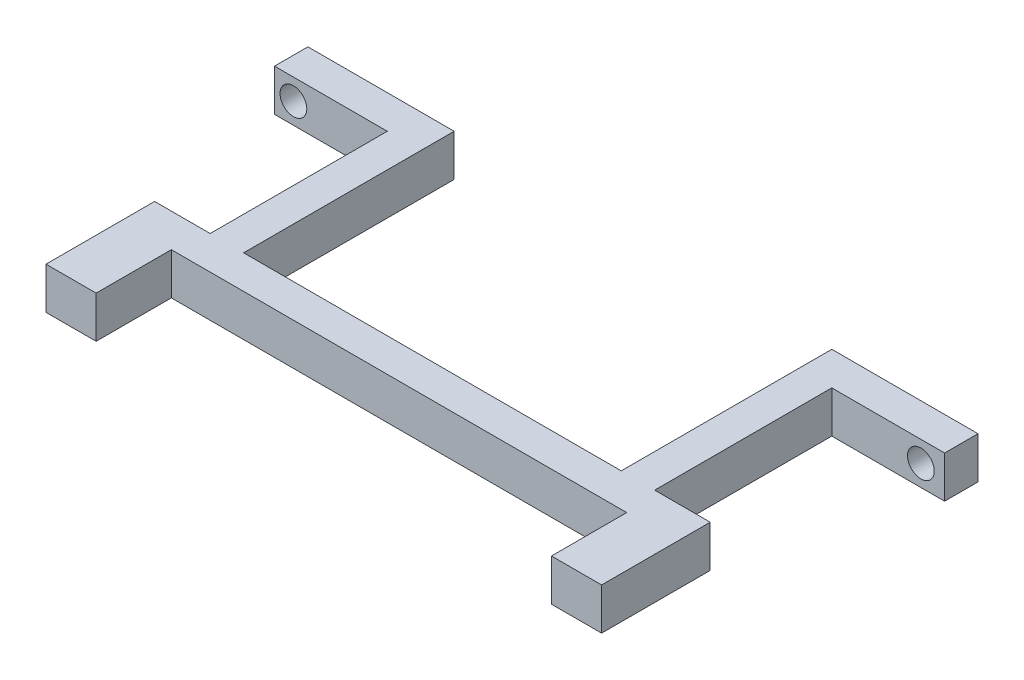
SolidWorks part; units mm, degrees
ref_plane "Front Plane" through (0, 0, 0) normal (0, 0, 1) x (1, 0, 0)
ref_plane "Top Plane" through (0, 0, 0) normal (0, 1, 0) x (1, 0, 0)
ref_plane "Right Plane" through (0, 0, 0) normal (1, 0, 0) x (0, 0, -1)
sketch "Sketch1" plane through (0, 0, 0) normal (0, 0, 1) x (1, 0, 0)
  line L1 (-91.6826, 14.4689) -> (-41.4826, 14.4689)
  line L2 (-91.6826, 14.4689) -> (-91.6826, 9.4689)
  line L3 (-91.6826, 9.4689) -> (-41.4826, 9.4689)
  line L4 (-41.4826, 14.4689) -> (-41.4826, 9.4689)
  dimension "D1" = 50.2
  dimension "D2" = 5
extrude "Boss-Extrude1" add sketch "Sketch1" along normal blind 26.2
sketch "Sketch2" plane through (0, 9.4689, 0) normal (0, -1, 0) x (1, 0, 0)
  line L0 (2.75, 0) -> (-2.75, 0) construction
  line L1 (-89.1826, 23.6998) -> (-43.9826, 23.6998)
  line L2 (-89.1826, 23.6998) -> (-89.1826, 0)
  line L3 (-89.1826, 0) -> (-43.9826, 0)
  line L4 (-43.9826, 23.6998) -> (-43.9826, 0)
  line L5 (-91.6826, 26.2) -> (-91.6826, 0) construction
  dimension "D1" = 45.2
  dimension "D2" = 2.5
extrude "Cut-Extrude1" cut sketch "Sketch2" against normal blind 26.2
sketch "Sketch4" plane through (0, 9.4689, 0) normal (0, -1, 0) x (1, 0, 0)
  line L1 (-91.6826, 26.2) -> (-90.1826, 26.2)
  line L2 (-91.6826, 26.2) -> (-91.6826, 2)
  line L3 (-91.6826, 2) -> (-90.1826, 2)
  line L4 (-90.1826, 26.2) -> (-90.1826, 2)
  dimension "D1" = 24.2
  dimension "D2" = 1.5
extrude "Cut-Extrude2" cut sketch "Sketch4" against normal blind 26.2
sketch "Sketch5" plane through (-91.6826, 0, 0) normal (-1, 0, 0) x (0, 0, 1)
  line L0 (0, -2.75) -> (0, 2.75) construction
  line L1 (2, 14.4689) -> (0, 14.4689)
  line L2 (2, 14.4689) -> (2, 9.4689)
  line L3 (2, 9.4689) -> (0, 9.4689)
  line L4 (0, 14.4689) -> (0, 9.4689)
  line L5 (2, 9.4689) -> (0, 9.4689) construction
extrude "Boss-Extrude2" add sketch "Sketch5" along normal blind 3
sketch "Sketch7" plane through (0, 9.4689, 0) normal (0, -1, 0) x (1, 0, 0)
  line L1 (-41.4826, 26.2) -> (-42.9826, 26.2)
  line L2 (-41.4826, 26.2) -> (-41.4826, 2)
  line L3 (-41.4826, 2) -> (-42.9826, 2)
  line L4 (-42.9826, 26.2) -> (-42.9826, 2)
  dimension "D1" = 1.5
  dimension "D2" = 24.2
extrude "Cut-Extrude3" cut sketch "Sketch7" against normal blind 23
sketch "Sketch8" plane through (0, 9.4689, 0) normal (0, -1, 0) x (1, 0, 0)
  line L1 (-89.1826, 23.6998) -> (-43.9826, 23.6998)
  line L2 (-89.1826, 23.6998) -> (-89.1826, 25.1998)
  line L3 (-89.1826, 25.1998) -> (-43.9826, 25.1998)
  line L4 (-43.9826, 23.6998) -> (-43.9826, 25.1998)
  dimension "D1" = 45.2
  dimension "D2" = 1.5
extrude "Cut-Extrude4" cut sketch "Sketch8" against normal blind 23
sketch "Sketch9" plane through (-41.4826, 0, 0) normal (1, 0, 0) x (0, 0, -1)
  line L0 (0, 2.75) -> (0, -2.75) construction
  line L1 (-2, 14.4689) -> (0, 14.4689)
  line L2 (-2, 14.4689) -> (-2, 9.4689)
  line L3 (-2, 9.4689) -> (0, 9.4689)
  line L4 (0, 14.4689) -> (0, 9.4689)
  line L5 (-2, 9.4689) -> (0, 9.4689) construction
extrude "Boss-Extrude3" add sketch "Sketch9" along normal blind 3
sketch "Sketch11" plane through (-38.4826, 0, 0) normal (1, 0, 0) x (0, 0, -1)
  line L0 (0, 2.75) -> (0, -2.75) construction
  line L1 (-2, 14.4689) -> (0, 14.4689)
  line L2 (-2, 14.4689) -> (-2, 9.4689)
  line L3 (-2, 9.4689) -> (0, 9.4689)
  line L4 (0, 14.4689) -> (0, 9.4689)
  line L5 (-2, 9.4689) -> (0, 9.4689) construction
extrude "Boss-Extrude4" add sketch "Sketch11" along normal blind 2
sketch "Sketch12" plane through (-94.6826, 0, 0) normal (-1, 0, 0) x (0, 0, 1)
  line L0 (0, -2.75) -> (0, 2.75) construction
  line L1 (2, 14.4689) -> (0, 14.4689)
  line L2 (2, 14.4689) -> (2, 9.4716)
  line L3 (2, 9.4716) -> (0, 9.4716)
  line L4 (0, 14.4689) -> (0, 9.4716)
extrude "Boss-Extrude5" add sketch "Sketch12" along normal blind 2
sketch "Sketch15" plane through (-90.1826, 0, 0) normal (-1, 0, 0) x (0, 0, 1)
  line L0 (2, 9.4689) -> (26.2, 9.4689) construction
  line L1 (26.2, 14.4689) -> (25.2, 14.4689)
  line L2 (26.2, 14.4689) -> (26.2, 9.4689)
  line L3 (26.2, 9.4689) -> (25.2, 9.4689)
  line L4 (25.2, 14.4689) -> (25.2, 9.4689)
  dimension "D1" = 1
extrude "Boss-Extrude6" add sketch "Sketch15" along normal blind 4.65
sketch "Sketch16" plane through (-42.9826, 0, 0) normal (1, 0, 0) x (0, 0, -1)
  line L0 (-26.2, 9.4689) -> (-2, 9.4689) construction
  line L1 (-26.2, 14.4689) -> (-25.2, 14.4689)
  line L2 (-26.2, 14.4689) -> (-26.2, 9.4689)
  line L3 (-26.2, 9.4689) -> (-25.2, 9.4689)
  line L4 (-25.2, 14.4689) -> (-25.2, 9.4689)
  dimension "D1" = 1
extrude "Boss-Extrude7" add sketch "Sketch16" along normal blind 4.65
sketch "Sketch17" plane through (0, 0, 26.2) normal (0, 0, 1) x (1, 0, 0)
  line L0 (-94.8326, 9.4689) -> (-38.3326, 9.4689) construction
  line L1 (-38.3326, 14.4689) -> (-39.3326, 14.4689)
  line L2 (-38.3326, 14.4689) -> (-38.3326, 9.4689)
  line L3 (-38.3326, 9.4689) -> (-39.3326, 9.4689)
  line L4 (-39.3326, 14.4689) -> (-39.3326, 9.4689)
  dimension "D1" = 1
extrude "Boss-Extrude8" add sketch "Sketch17" along normal blind 9
sketch "Sketch18" plane through (0, 0, 26.2) normal (0, 0, 1) x (1, 0, 0)
  line L0 (-94.8326, 9.4689) -> (-39.3326, 9.4689) construction
  line L1 (-94.8326, 14.4689) -> (-93.8326, 14.4689)
  line L2 (-94.8326, 14.4689) -> (-94.8326, 9.4689)
  line L3 (-94.8326, 9.4689) -> (-93.8326, 9.4689)
  line L4 (-93.8326, 14.4689) -> (-93.8326, 9.4689)
  dimension "D1" = 1
extrude "Boss-Extrude9" add sketch "Sketch18" along normal blind 9
sketch "Sketch20" plane through (-94.8326, 0, 0) normal (-1, 0, 0) x (0, 0, 1)
  line L1 (25.2, 14.4689) -> (35.2, 14.4689)
  line L2 (25.2, 14.4689) -> (25.2, 9.4689)
  line L3 (25.2, 9.4689) -> (35.2, 9.4689)
  line L4 (35.2, 14.4689) -> (35.2, 9.4689)
extrude "Boss-Extrude10" add sketch "Sketch20" along normal blind 2
sketch "Sketch21" plane through (-38.3326, 0, 0) normal (1, 0, 0) x (0, 0, -1)
  line L1 (-35.2, 14.4689) -> (-25.2, 14.4689)
  line L2 (-35.2, 14.4689) -> (-35.2, 9.4689)
  line L3 (-35.2, 9.4689) -> (-25.2, 9.4689)
  line L4 (-25.2, 14.4689) -> (-25.2, 9.4689)
extrude "Boss-Extrude11" add sketch "Sketch21" along normal blind 2
sketch "Sketch22" plane through (-90.1826, 0, 0) normal (-1, 0, 0) x (0, 0, 1)
  line L1 (2, 14.4689) -> (25.2, 14.4689)
  line L2 (2, 14.4689) -> (2, 9.4689)
  line L3 (2, 9.4689) -> (25.2, 9.4689)
  line L4 (25.2, 14.4689) -> (25.2, 9.4689)
extrude "Boss-Extrude12" add sketch "Sketch22" along normal blind 3
sketch "Sketch23" plane through (-42.9826, 0, 0) normal (1, 0, 0) x (0, 0, -1)
  line L1 (-25.2, 14.4689) -> (-2, 14.4689)
  line L2 (-25.2, 14.4689) -> (-25.2, 9.4689)
  line L3 (-25.2, 9.4689) -> (-2, 9.4689)
  line L4 (-2, 14.4689) -> (-2, 9.4689)
extrude "Boss-Extrude13" add sketch "Sketch23" along normal blind 3
sketch "Sketch24" plane through (0, 0, 26.2) normal (0, 0, 1) x (1, 0, 0)
  line L1 (-93.8326, 14.4689) -> (-39.3326, 14.4689)
  line L2 (-93.8326, 14.4689) -> (-93.8326, 9.4689)
  line L3 (-93.8326, 9.4689) -> (-39.3326, 9.4689)
  line L4 (-39.3326, 14.4689) -> (-39.3326, 9.4689)
extrude "Boss-Extrude14" add sketch "Sketch24" along normal blind 3
sketch "Sketch25" plane through (0, 0, 35.2) normal (0, 0, 1) x (1, 0, 0)
  line L1 (-39.3326, 14.4689) -> (-36.3326, 14.4689)
  line L2 (-39.3326, 14.4689) -> (-39.3326, 9.4689)
  line L3 (-39.3326, 9.4689) -> (-36.3326, 9.4689)
  line L4 (-36.3326, 14.4689) -> (-36.3326, 9.4689)
extrude "Boss-Extrude15" add sketch "Sketch25" along normal blind 3
sketch "Sketch26" plane through (0, 0, 35.2) normal (0, 0, 1) x (1, 0, 0)
  line L1 (-96.8326, 14.4689) -> (-93.8326, 14.4689)
  line L2 (-96.8326, 14.4689) -> (-96.8326, 9.4689)
  line L3 (-96.8326, 9.4689) -> (-93.8326, 9.4689)
  line L4 (-93.8326, 14.4689) -> (-93.8326, 9.4689)
extrude "Boss-Extrude16" add sketch "Sketch26" along normal blind 3
sketch "Sketch27" plane through (-96.8326, 0, 0) normal (-1, 0, 0) x (0, 0, 1)
  line L1 (25.2, 14.4689) -> (38.2, 14.4689)
  line L2 (25.2, 14.4689) -> (25.2, 9.4689)
  line L3 (25.2, 9.4689) -> (38.2, 9.4689)
  line L4 (38.2, 14.4689) -> (38.2, 9.4689)
extrude "Boss-Extrude17" add sketch "Sketch27" along normal blind 3
sketch "Sketch28" plane through (-36.3326, 0, 0) normal (1, 0, 0) x (0, 0, -1)
  line L1 (-38.2, 14.4689) -> (-25.2, 14.4689)
  line L2 (-38.2, 14.4689) -> (-38.2, 9.4689)
  line L3 (-38.2, 9.4689) -> (-25.2, 9.4689)
  line L4 (-25.2, 14.4689) -> (-25.2, 9.4689)
extrude "Boss-Extrude18" add sketch "Sketch28" along normal blind 3
sketch "Sketch29" plane through (-36.4826, 0, 0) normal (1, 0, 0) x (0, 0, -1)
  line L1 (-2, 14.4689) -> (0, 14.4689)
  line L2 (-2, 14.4689) -> (-2, 9.4689)
  line L3 (-2, 9.4689) -> (0, 9.4689)
  line L4 (0, 14.4689) -> (0, 9.4689)
extrude "Boss-Extrude21" add sketch "Sketch29" along normal blind 10
sketch "Sketch30" plane through (-96.6826, 0, 0) normal (-1, 0, 0) x (0, 0, 1)
  line L1 (0, 14.4689) -> (2, 14.4689)
  line L2 (0, 14.4689) -> (0, 9.4716)
  line L3 (0, 9.4716) -> (2, 9.4716)
  line L4 (2, 14.4689) -> (2, 9.4716)
extrude "Boss-Extrude22" add sketch "Sketch30" along normal blind 10
sketch "Sketch31" plane through (0, 0, 2) normal (0, 0, 1) x (1, 0, 0)
  line L1 (-106.6826, 14.4689) -> (-93.1826, 14.4689)
  line L2 (-106.6826, 14.4689) -> (-106.6826, 9.4689)
  line L3 (-106.6826, 9.4689) -> (-93.1826, 9.4689)
  line L4 (-93.1826, 14.4689) -> (-93.1826, 9.4689)
extrude "Boss-Extrude23" add sketch "Sketch31" along normal blind 2
sketch "Sketch32" plane through (0, 0, 2) normal (0, 0, 1) x (1, 0, 0)
  line L1 (-39.9826, 14.4689) -> (-26.4826, 14.4689)
  line L2 (-39.9826, 14.4689) -> (-39.9826, 9.4689)
  line L3 (-39.9826, 9.4689) -> (-26.4826, 9.4689)
  line L4 (-26.4826, 14.4689) -> (-26.4826, 9.4689)
extrude "Boss-Extrude24" add sketch "Sketch32" along normal blind 2
sketch "Sketch33" plane through (0, 0, 4) normal (0, 0, 1) x (1, 0, 0)
  line L0 (-106.6826, 11.9689) -> (-92.2278, 11.9689) construction
  line L1 (-106.6826, 14.4689) -> (-106.6826, 9.4689) construction
  circle A0 centre (-104.4198, 11.9689) radius 1.6
  dimension "D1" = 3.2
extrude "Cut-Extrude5" cut sketch "Sketch33" against normal blind 12
sketch "Sketch34" plane through (0, 0, 4) normal (0, 0, 1) x (1, 0, 0)
  line L0 (-26.4826, 11.9689) -> (-50.1129, 11.9689) construction
  line L1 (-26.4826, 9.4689) -> (-26.4826, 14.4689) construction
  circle A0 centre (-29.319, 11.9689) radius 1.6
  dimension "D1" = 3.2
extrude "Cut-Extrude6" cut sketch "Sketch34" against normal blind 12
